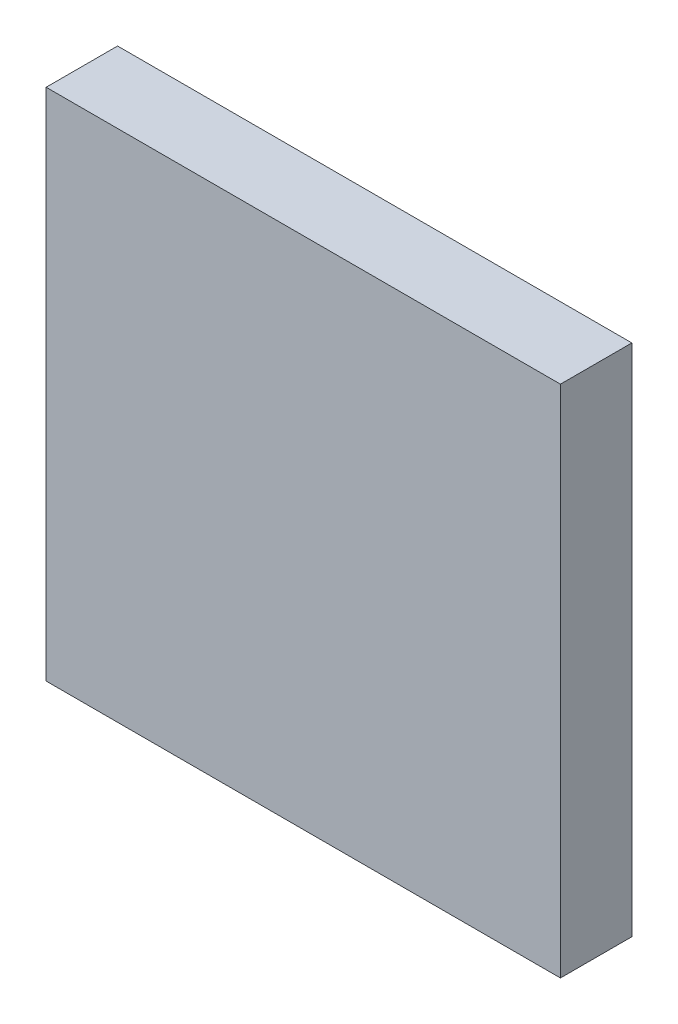
SolidWorks part; units mm, degrees
ref_plane "정면" through (0, 0, 0) normal (0, 0, 1) x (1, 0, 0)
ref_plane "윗면" through (0, 0, 0) normal (0, 1, 0) x (1, 0, 0)
ref_plane "우측면" through (0, 0, 0) normal (1, 0, 0) x (0, 0, -1)
sketch "스케치1" plane through (0, 0, 0) normal (0, 0, 1) x (1, 0, 0)
  line L0 (-0.1541, -15.7576) -> (69.1581, -15.7576) construction
  line L1 (17.8459, 15.2791) -> (17.8459, -49.4231) construction
  line L5 (-0.1541, 2.2424) -> (35.8459, 2.2424)
  line L6 (-0.1541, 2.2424) -> (-0.1541, -33.7576)
  line L7 (-0.1541, -33.7576) -> (35.8459, -33.7576)
  line L8 (35.8459, 2.2424) -> (35.8459, -33.7576)
  circle A0 centre (2.5959, -0.5076) radius 2
  circle A1 centre (17.8459, -0.5076) radius 2
  circle A2 centre (33.0959, -0.5076) radius 2
  circle A3 centre (33.0959, -15.7576) radius 2
  circle A4 centre (33.0959, -31.0076) radius 2
  circle A5 centre (17.8459, -31.0076) radius 2
  circle A6 centre (2.5959, -31.0076) radius 2
  circle A7 centre (2.5959, -15.7576) radius 2
  point P24 (0, 0)
  point P25 (0, 0)
  dimension "D3" = 36
  dimension "D1" = 4
  dimension "D2" = 4
  dimension "D5" = 4
  dimension "D6" = 4
  dimension "D7" = 4
  dimension "D8" = 4
  dimension "D9" = 4
  dimension "D10" = 4
  dimension "D4" = 36
  dimension "D11" = 15.25
  dimension "D12" = 15.25
  dimension "D13" = 15.25
  dimension "D14" = 15.25
  dimension "D15" = 15.25
  dimension "D16" = 18
  dimension "D17" = 15.25
  dimension "D18" = 15.25
  dimension "D19" = 15.25
  dimension "D20" = 15.25
  dimension "D21" = 15.25
  dimension "D22" = 15.25
  dimension "D23" = 15.25
  dimension "D24" = 15.25
  dimension "D25" = 15.25
  dimension "D26" = 15.25
  dimension "D27" = 15.25
extrude "보스-돌출1" add sketch "스케치1" along normal blind 3
sketch "스케치2" plane through (0, 0, 3) normal (0, 0, 1) x (1, 0, 0)
  line L1 (-0.1541, 2.2424) -> (35.8459, 2.2424)
  line L2 (-0.1541, 2.2424) -> (-0.1541, -33.7576)
  line L3 (-0.1541, -33.7576) -> (35.8459, -33.7576)
  line L4 (35.8459, 2.2424) -> (35.8459, -33.7576)
extrude "보스-돌출2" add sketch "스케치2" along normal blind 2
